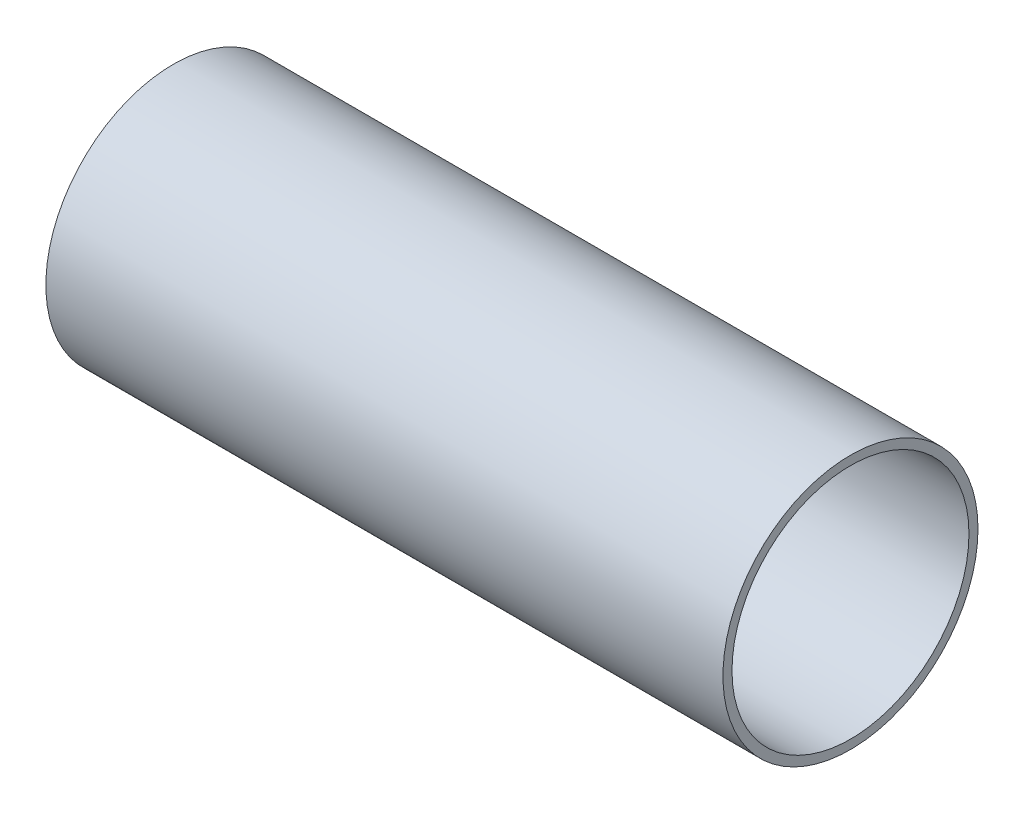
SolidWorks part; units mm, degrees
ref_plane "Front Plane" through (0, 0, 0) normal (0, 0, 1) x (1, 0, 0)
ref_plane "Top Plane" through (0, 0, 0) normal (0, 1, 0) x (1, 0, 0)
ref_plane "Right Plane" through (0, 0, 0) normal (1, 0, 0) x (0, 0, -1)
sketch "Sketch1" plane through (0, 0, 0) normal (1, 0, 0) x (0, 0, -1)
  circle A0 centre (0, 0) radius 52.5
  circle A1 centre (0, 0) radius 56.5
  dimension "D1" = 105
  dimension "D2" = 4
extrude "Boss-Extrude1" add sketch "Sketch1" along normal blind 300
